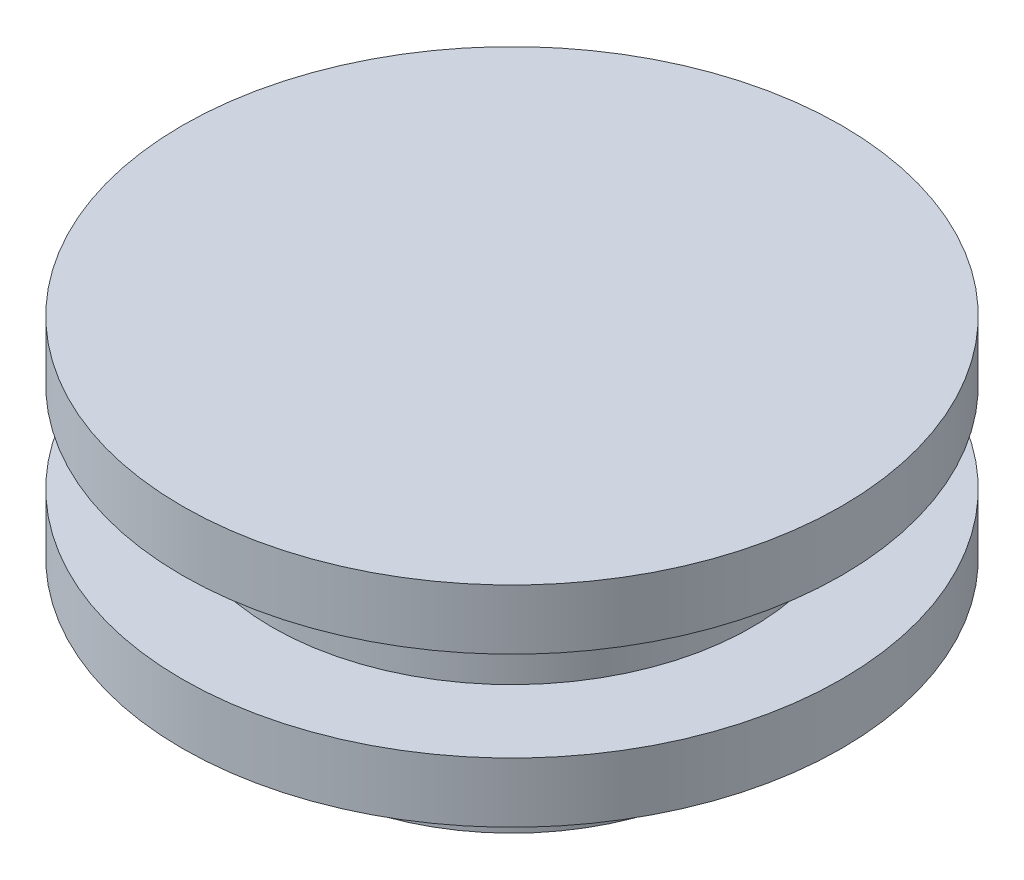
SolidWorks part; units mm, degrees
material "PA Tipo 6"
ref_plane "Alzado" through (0, 0, 0) normal (0, 0, 1) x (1, 0, 0)
ref_plane "Planta" through (0, 0, 0) normal (0, 1, 0) x (1, 0, 0)
ref_plane "Vista lateral" through (0, 0, 0) normal (1, 0, 0) x (0, 0, -1)
sketch "Croquis1" plane through (0, 0, 0) normal (0, 0, 1) x (1, 0, 0)
  line L0 (0, 5.112) -> (0, -2.8548) construction
  line L1 (3.5, -2.5) -> (5.5, -2.5)
  line L2 (3.5, -4) -> (3.5, -2.5)
  line L3 (5.5, -2.5) -> (5.5, -1.5)
  line L4 (5.5, -1.5) -> (4, -1.5)
  line L5 (4, -1.5) -> (4, 0)
  line L6 (4, 0) -> (5.5, 0)
  line L7 (5.5, 0) -> (5.5, 1)
  line L8 (5.5, 1) -> (0, 1)
  line L9 (3.5, -4) -> (2.5, -4)
  line L10 (2.5, -4) -> (2.5, -1)
  line L11 (2.5, -1) -> (0, -1)
  line L12 (0, -1) -> (0, 1)
  point P3 (0, 0)
  dimension "D1" = 1
  dimension "D2" = 2
  dimension "D3" = 1
  dimension "D4" = 1.5
  dimension "D5" = 1.5
  dimension "D6" = 3
  dimension "D7" = 2.5
  dimension "D8" = 1.5
revolve "Revolución1" add sketch "Croquis1" angle 360 about L0
